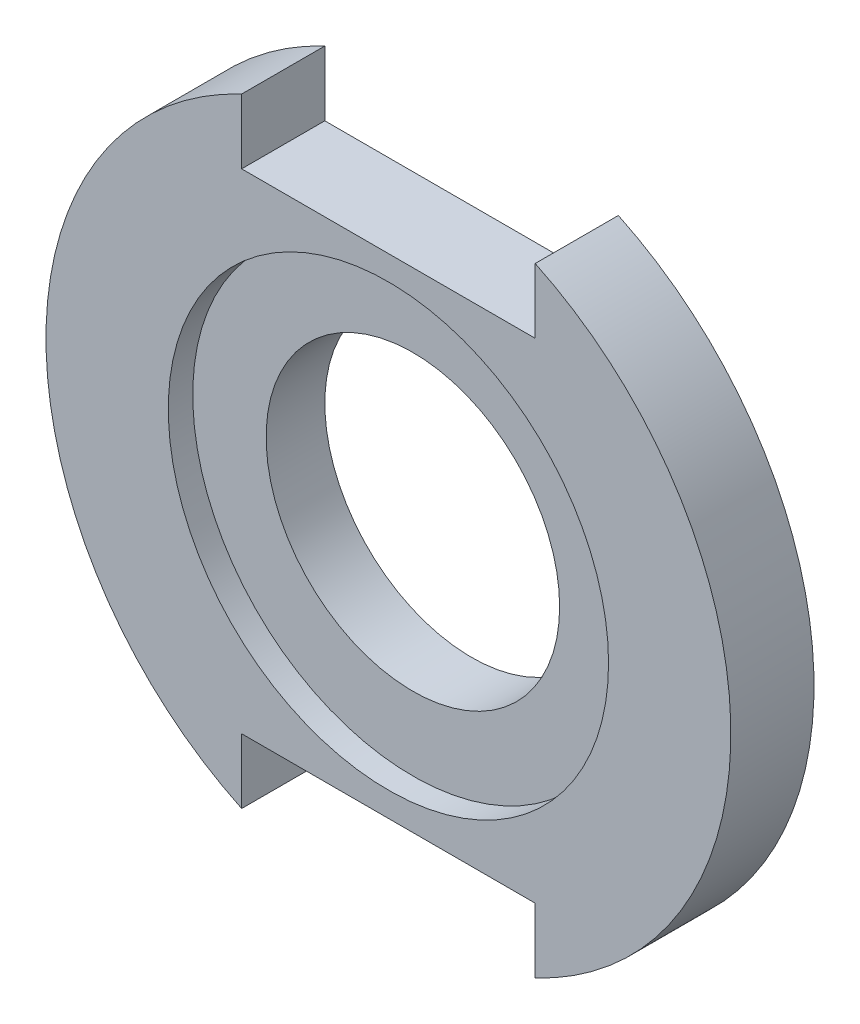
SolidWorks part; units mm, degrees
ref_plane "정면" through (0, 0, 0) normal (0, 0, 1) x (1, 0, 0)
ref_plane "윗면" through (0, 0, 0) normal (0, 1, 0) x (1, 0, 0)
ref_plane "우측면" through (0, 0, 0) normal (1, 0, 0) x (0, 0, -1)
sketch "스케치1" plane through (0, 0, 0) normal (0, 0, 1) x (1, 0, 0)
  circle A0 centre (0, 0) radius 14
  dimension "D1" = 28
extrude "보스-돌출1" add sketch "스케치1" along normal blind 3.4
sketch "스케치2" plane through (0, 0, 3.4) normal (0, 0, 1) x (1, 0, 0)
  circle A0 centre (0, 0) radius 6
  dimension "D1" = 12
extrude "컷-돌출1" cut sketch "스케치2" against normal blind 3.4
sketch "스케치3" plane through (0, 0, 3.4) normal (0, 0, 1) x (1, 0, 0)
  line L1 (-6, 18) -> (6, 18)
  line L2 (-6, 18) -> (-6, 10)
  line L3 (-6, 10) -> (6, 10)
  line L4 (6, 18) -> (6, 10)
  line L5 (-6, 18) -> (6, 10) construction
  line L6 (-6, 10) -> (6, 18) construction
  line L7 (-6, -18) -> (6, -18)
  line L8 (-6, -18) -> (-6, -10)
  line L9 (-6, -10) -> (6, -10)
  line L10 (6, -18) -> (6, -10)
  line L11 (-6, -18) -> (6, -10) construction
  line L12 (-6, -10) -> (6, -18) construction
  circle A0 centre (0, 0) radius 14 construction
  point P0 (0, 14)
  point P7 (0, -14)
  dimension "D1" = 12
  dimension "D2" = 12
  dimension "D3" = 4
  dimension "D4" = 4
  dimension "D5" = 6
  dimension "D6" = 6
extrude "컷-돌출2" cut sketch "스케치3" against normal blind 3.4
sketch "스케치4" plane through (0, 0, 3.4) normal (0, 0, 1) x (1, 0, 0)
  circle A0 centre (0, 0) radius 9
  dimension "D1" = 18
extrude "컷-돌출3" cut sketch "스케치4" against normal blind 1
